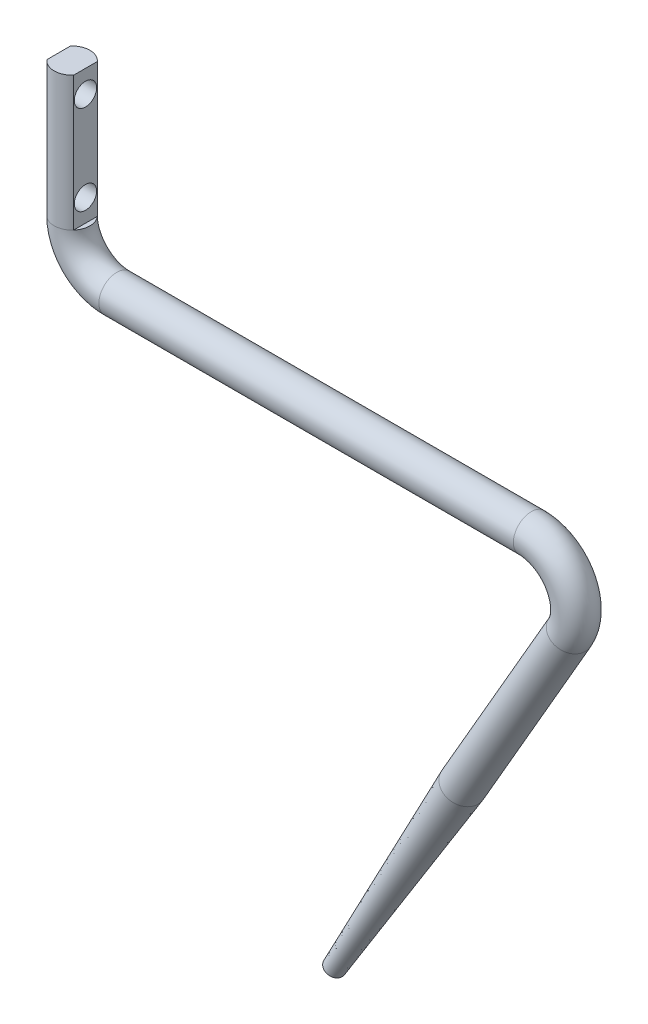
SolidWorks part; units mm, degrees
material "AISI 304"
ref_plane "前视基准面" through (0, 0, 0) normal (0, 0, 1) x (1, 0, 0)
ref_plane "上视基准面" through (0, 0, 0) normal (0, 1, 0) x (1, 0, 0)
ref_plane "右视基准面" through (0, 0, 0) normal (1, 0, 0) x (0, 0, -1)
sketch "Sketch1" plane through (0, 0, 0) normal (0, 0, 1) x (1, 0, 0)
  line L0 (0, 40) -> (0, 10)
  line L1 (10, 0) -> (102.6787, 0)
  line L2 (111.3388, -15.0003) -> (58.68, -106.2)
  arc A0 (102.6787, 0) -> (111.3388, -15.0003) centre (102.6787, -10) cw
  arc A1 (0, 10) -> (10, 0) centre (10, 10) ccw
  point P7 (120, 0)
  point P10 (0, 0)
  dimension "D5" = 10
  dimension "D1" = 40
  dimension "D2" = 120
  dimension "D3" = 106.2
  dimension "D4" = 61.32
ref_plane "Plane1" through (0, 40, 0) normal (0, 1, 0) x (1, 0, 0)
sketch "Sketch3" plane through (0, 40, 0) normal (0, 1, 0) x (1, 0, 0)
  circle A0 centre (0, 0) radius 4
  dimension "D1" = 8
sweep "Sweep1" add profiles "Sketch3" path "Sketch1"
chamfer "Chamfer1" distance 2 angle 88 1 edges at (58.68, -106.2, 4)
sketch "Sketch4" plane through (0, 40, 0) normal (0, 1, 0) x (1, 0, 0)
  line L1 (3, 17.7651) -> (-3, 17.7651)
  line L2 (3, 17.7651) -> (3, -17.7651)
  line L3 (3, -17.7651) -> (-3, -17.7651)
  line L4 (-3, 17.7651) -> (-3, -17.7651)
  line L5 (3, 17.7651) -> (-3, -17.7651) construction
  line L6 (3, -17.7651) -> (-3, 17.7651) construction
  point P0 (0, 0)
  dimension "D1" = 3
extrude "Extrude1" cut sketch "Sketch4" against normal blind 30 flip side to cut
hole_wizard "M6 Tapped Hole1" positions "Sketch5" profile "Sketch6" tap size "M6" standard "GB"
sketch "Sketch5" plane through (3, 0, 0) normal (1, 0, 0) x (0, 0, -1)
  line L0 (-2.6458, 10) -> (2.6458, 10) construction
  point P0 (0, 35)
  point P2 (0, 15)
  dimension "D1" = 20
  dimension "D2" = 5
sketch "Sketch6" plane through (3, 35, 0) normal (0, 1, 0) x (0, 0, -1)
  line L0 (0, 0) -> (0, 10.5022)
  line L1 (0, 10.5022) -> (2.5, 9)
  line L2 (2.5, 9) -> (2.5, 0)
  line L5 (2.5, 0) -> (0, 0)
  line L10 (0, 10.5022) -> (-2.5, 9) construction
  line L11 (0, -6.35) -> (0, 107.95) construction
  dimension "螺纹孔钻头直径" = 5
  dimension "螺纹孔钻头深度" = 9
  dimension "导头角度" = 118
